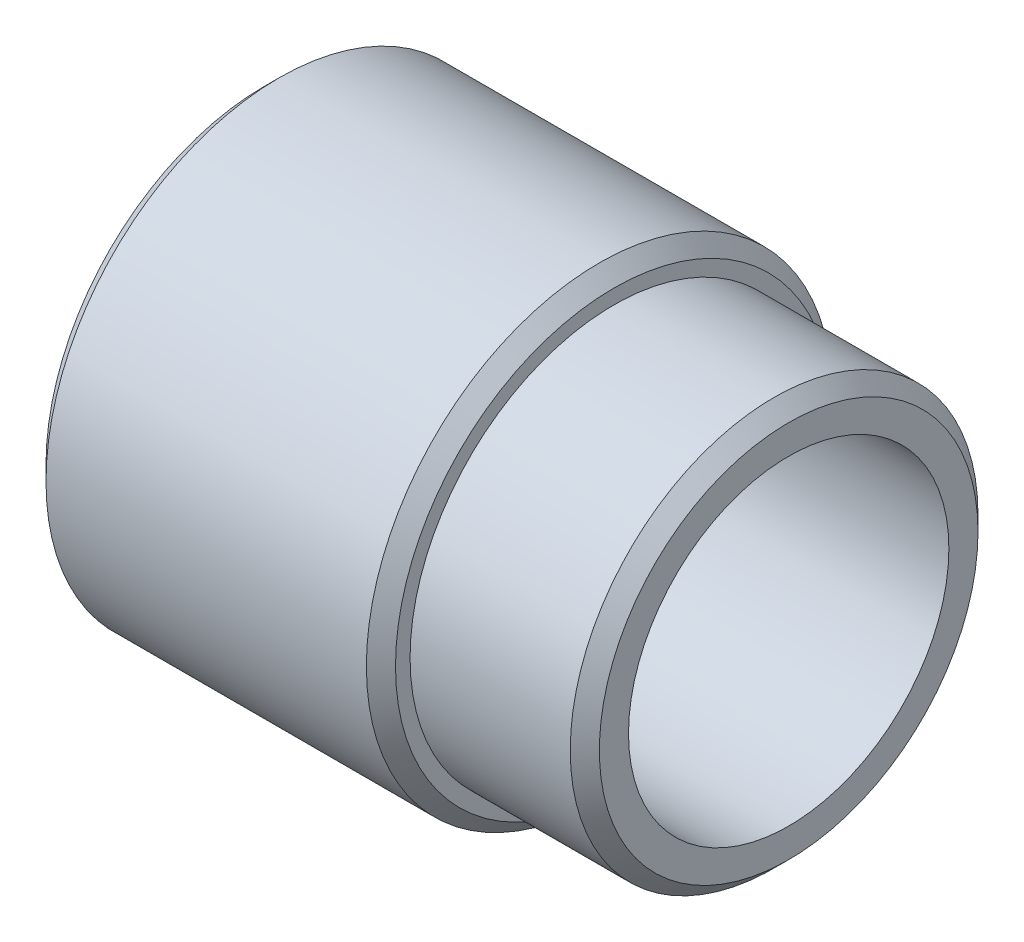
SolidWorks part; units mm, degrees
material "AISI 304"
ref_plane "Спереди" through (0, 0, 0) normal (0, 0, 1) x (1, 0, 0)
ref_plane "Сверху" through (0, 0, 0) normal (0, 1, 0) x (1, 0, 0)
ref_plane "Справа" through (0, 0, 0) normal (1, 0, 0) x (0, 0, -1)
sketch "Эскиз1" plane through (0, 0, 0) normal (0, 0, 1) x (1, 0, 0)
  line L0 (0, 0) -> (25.1038, 0) construction
  line L1 (0, 5.5) -> (20, 5.5)
  line L2 (20, 5.5) -> (20, 9)
  line L3 (20, 9) -> (18, 9)
  line L4 (18, 9) -> (18, 7)
  line L5 (18, 7) -> (0, 7)
  line L6 (0, 7) -> (0, 5.5)
  dimension "D1" = 11
  dimension "D2" = 14
  dimension "D3" = 18
  dimension "D4" = 2
  dimension "D5" = 18
revolve "Повернуть1" add sketch "Эскиз1" angle 360 about L0
sketch "Эскиз4" plane through (20, 0, 0) normal (1, 0, 0) x (0, 0, -1)
  circle A0 centre (0, 0) radius 9
extrude "Вырез-Вытянуть1" cut sketch "Эскиз4" against normal up to surface (2 mm away) up to face at (18, 0, 7)
sketch "Эскиз5" plane through (0, 0, 0) normal (-1, 0, 0) x (0, 0, 1)
  circle A0 centre (0, 0) radius 8
  circle A1 centre (0, 0) radius 5.5
  dimension "D1" = 16
  dimension "D2" = 11
extrude "Бобышка-Вытянуть1" add sketch "Эскиз5" against normal blind 12
chamfer "Фаска1" distance 0.5 angle 45 3 edges at (18, 0, -7) (12, 0, 8) (0, 0, 8)
